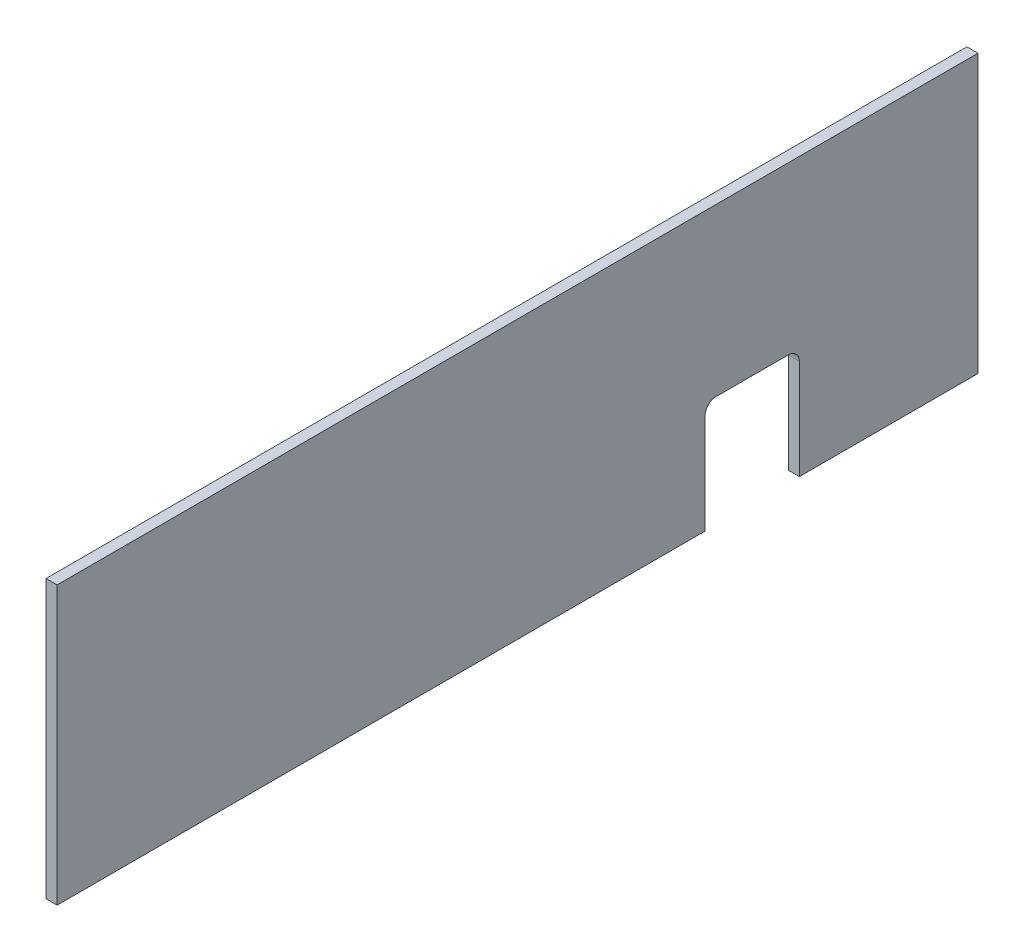
SolidWorks part; units mm, degrees
ref_plane "Front Plane" through (0, 0, 0) normal (0, 0, 1) x (1, 0, 0)
ref_plane "Top Plane" through (0, 0, 0) normal (0, 1, 0) x (1, 0, 0)
ref_plane "Right Plane" through (0, 0, 0) normal (1, 0, 0) x (0, 0, -1)
sketch "Sketch1" plane through (0, 0, 0) normal (1, 0, 0) x (0, 0, -1)
  line L1 (-41.5, -12.5) -> (41.5, -12.5)
  line L2 (-41.5, -12.5) -> (-41.5, 12.5)
  line L3 (-41.5, 12.5) -> (41.5, 12.5)
  line L4 (41.5, -12.5) -> (41.5, 12.5)
  line L5 (-41.5, -12.5) -> (41.5, 12.5) construction
  line L6 (-41.5, 12.5) -> (41.5, -12.5) construction
  line L7 (16.9, -12.5) -> (25.4, -12.5)
  line L8 (16.9, -12.5) -> (16.9, -2.5)
  line L9 (16.9, -2.5) -> (25.4, -2.5)
  line L10 (25.4, -12.5) -> (25.4, -2.5)
  point P0 (0, 0)
  dimension "D1" = 25
  dimension "D2" = 83
  dimension "D3" = 8.5
  dimension "D4" = 10
  dimension "D5" = 16.1
extrude "Boss-Extrude1" add sketch "Sketch1" along normal blind 1 contours L10 L1 L4 L3 L2 L8 L9
fillet "Fillet1" radius 1 2 edges at (0.5, -2.5, -16.9) (0.5, -2.5, -25.4)
